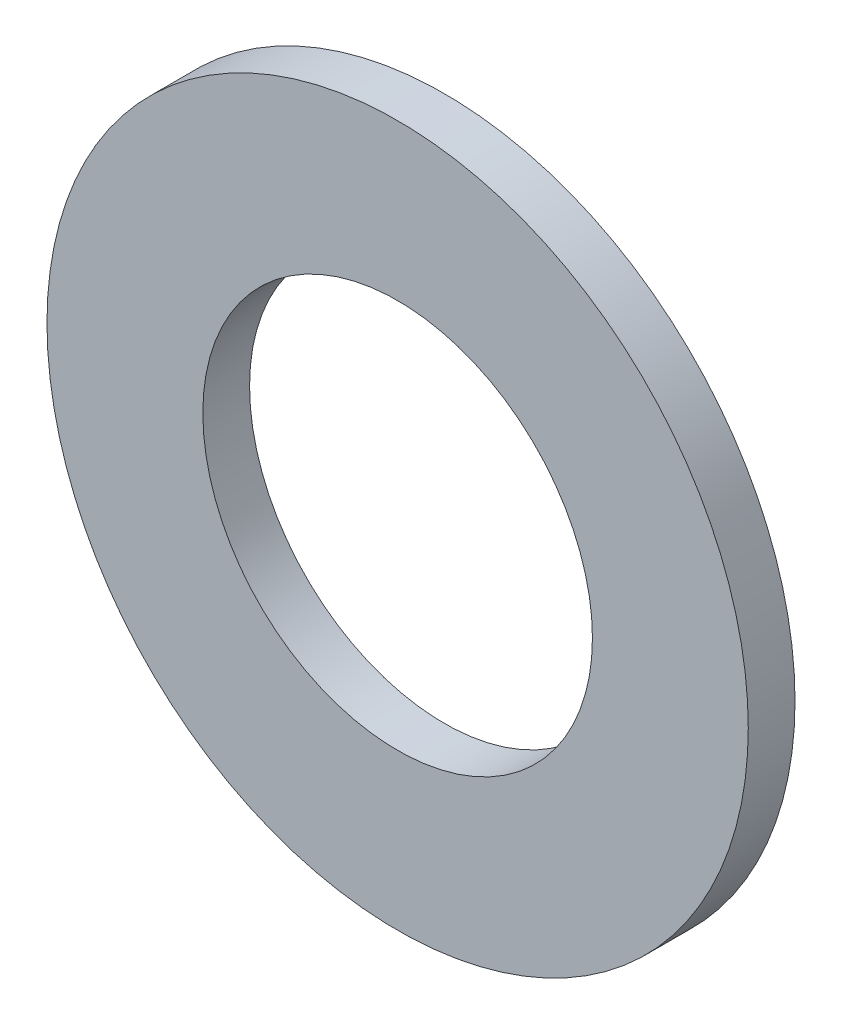
SolidWorks part; units mm, degrees
ref_plane "Front Plane" through (0, 0, 0) normal (0, 0, 1) x (1, 0, 0)
ref_plane "Top Plane" through (0, 0, 0) normal (0, 1, 0) x (1, 0, 0)
ref_plane "Right Plane" through (0, 0, 0) normal (1, 0, 0) x (0, 0, -1)
sketch "Sketch1" plane through (0, 0, 0) normal (0, 0, 1) x (1, 0, 0)
  circle A0 centre (0, 0) radius 12.5
  circle A1 centre (0, 0) radius 22.5
  dimension "D1" = 25
  dimension "D2" = 45
extrude "Boss-Extrude1" add sketch "Sketch1" along normal blind 3
